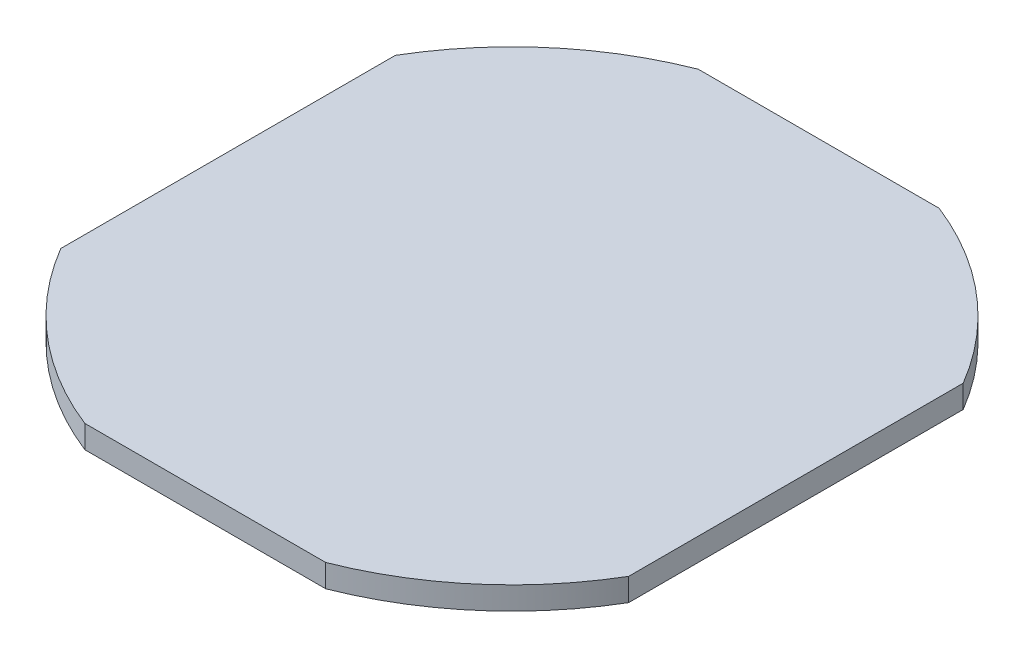
SolidWorks part; units mm, degrees
ref_plane "Front Plane" through (0, 0, 0) normal (0, 0, 1) x (1, 0, 0)
ref_plane "Top Plane" through (0, 0, 0) normal (0, 1, 0) x (1, 0, 0)
ref_plane "Right Plane" through (0, 0, 0) normal (1, 0, 0) x (0, 0, -1)
sketch "Sketch1" plane through (0, 0, 0) normal (0, 1, 0) x (1, 0, 0)
  line L1 (-26.4102, -67.25) -> (26.4102, -67.25)
  line L2 (-62.25, -36.6742) -> (-62.25, 36.6742)
  line L3 (-26.4102, 67.25) -> (26.4102, 67.25)
  line L4 (62.25, -36.6742) -> (62.25, 36.6742)
  line L5 (-62.25, -67.25) -> (62.25, 67.25) construction
  line L6 (-62.25, 67.25) -> (62.25, -67.25) construction
  arc A0 (-26.4102, 67.25) -> (-62.25, 36.6742) centre (0, 0) ccw
  arc A1 (62.25, 36.6742) -> (26.4102, 67.25) centre (0, 0) ccw
  arc A2 (-62.25, -36.6742) -> (-26.4102, -67.25) centre (0, 0) ccw
  arc A3 (26.4102, -67.25) -> (62.25, -36.6742) centre (0, 0) ccw
  dimension "D1" = 144.5
  dimension "D2" = 124.5
  dimension "D3" = 134.5
extrude "Boss-Extrude1" add sketch "Sketch1" along normal blind 5
